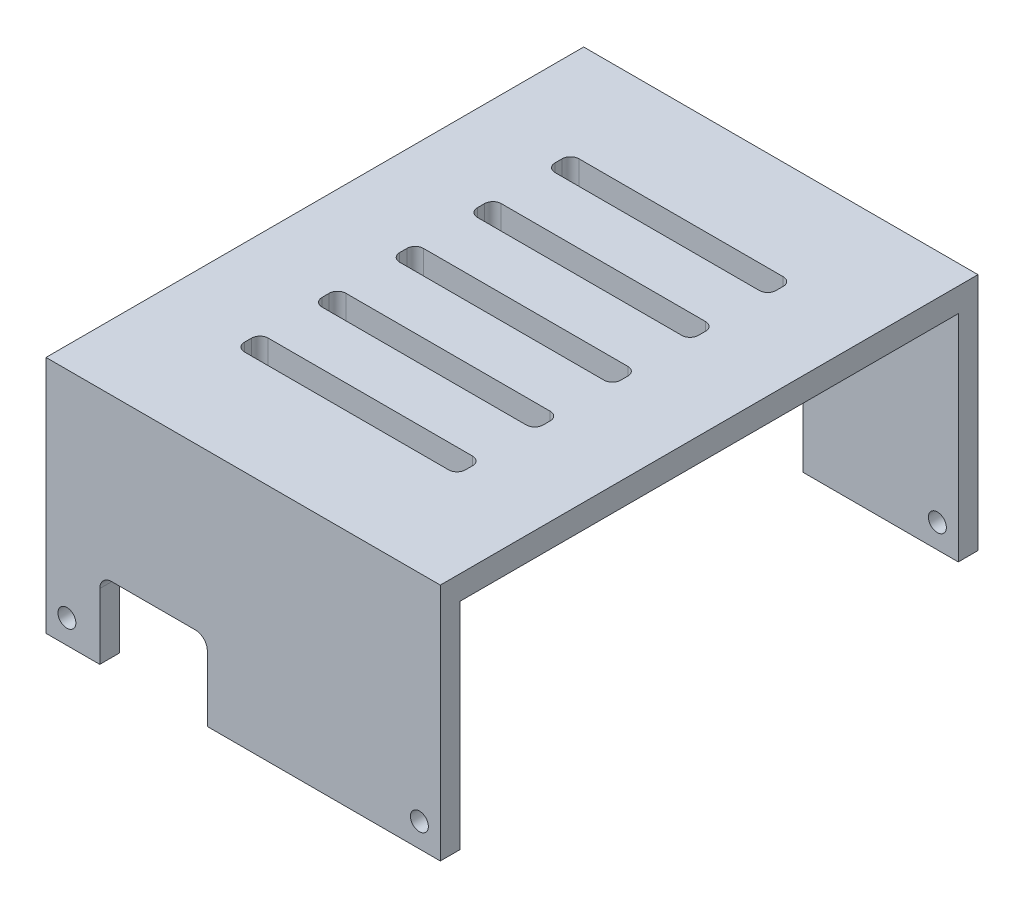
SolidWorks part; units mm, degrees
ref_plane "Front Plane" through (0, 0, 0) normal (0, 0, 1) x (1, 0, 0)
ref_plane "Top Plane" through (0, 0, 0) normal (0, 1, 0) x (1, 0, 0)
ref_plane "Right Plane" through (0, 0, 0) normal (1, 0, 0) x (0, 0, -1)
sketch "Sketch1" plane through (0, 0, 0) normal (0, 0, 1) x (1, 0, 0)
  line L1 (-33, -2) -> (33, -2)
  line L2 (-33, -2) -> (-33, 2)
  line L3 (-33, 2) -> (33, 2)
  line L4 (33, -2) -> (33, 2)
  line L5 (-33, -2) -> (33, 2) construction
  line L6 (-33, 2) -> (33, -2) construction
  point P0 (0, 0)
  dimension "D1" = 66
  dimension "D2" = 4
extrude "Boss-Extrude1" add sketch "Sketch1" along normal blind 90
sketch "Sketch2" plane through (0, 0, 90) normal (0, 0, 1) x (1, 0, 0)
  line L0 (-33, -2) -> (33, -2) construction
  line L1 (-33, -2) -> (33, -2)
  line L2 (-33, -2) -> (-33, -38)
  line L3 (-33, -38) -> (33, -38)
  line L4 (33, -2) -> (33, -38)
  point P6 (-30.5, -2)
  point P7 (30.2156, -2)
  point P8 (25.8419, -2)
  point P9 (0, 0)
  point P11 (30.5, -2)
  dimension "D3" = 36
extrude "Boss-Extrude2" add sketch "Sketch2" against normal blind 3.3
sketch "Sketch3" plane through (0, 0, 0) normal (0, 0, -1) x (-1, 0, 0)
  line L4 (33, -38) -> (33, -2)
  line L5 (33, -2) -> (-33, -2)
  line L6 (-33, -2) -> (-33, -38)
  line L7 (-33, -38) -> (33, -38)
  line L8 (33, -38) -> (33, -2)
  line L9 (33, -2) -> (-33, -2)
  line L10 (-33, -2) -> (-33, -38)
  line L11 (-33, -38) -> (33, -38)
  dimension "D1" = 0
extrude "Boss-Extrude3" add sketch "Sketch3" against normal blind 3.3
sketch "Sketch4" plane through (0, 0, 90) normal (0, 0, 1) x (1, 0, 0)
  line L0 (-33, -38) -> (33, -38) construction
  line L1 (-33, 2) -> (-33, -38) construction
  line L2 (33, -38) -> (33, 2) construction
  circle A0 centre (-29.5, -34) radius 1.5
  circle A1 centre (29.5, -34) radius 1.5
  point P4 (0, 0)
  dimension "D1" = 3
  dimension "D3" = 3.5
  dimension "D5" = 3
  dimension "D2" = 4
  dimension "D4" = 3.5
extrude "Cut-Extrude1" cut sketch "Sketch4" against normal through all
sketch "Sketch5" plane through (0, 0, 90) normal (0, 0, 1) x (1, 0, 0)
  line L0 (-15, -25) -> (-15, -38) construction
  line L1 (-24, -25) -> (-6, -25)
  line L2 (-24, -25) -> (-24, -38)
  line L3 (-24, -38) -> (-6, -38)
  line L4 (-6, -25) -> (-6, -38)
  line L5 (33, -38) -> (33, 2) construction
  line L6 (-33, -38) -> (33, -38) construction
  dimension "D1" = 18
  dimension "D2" = 48
  dimension "D3" = 13
extrude "Cut-Extrude2" cut sketch "Sketch5" against normal up to next
sketch "Sketch7" plane through (0, 0, 0) normal (0, 0, -1) x (-1, 0, 0)
  line L0 (-33, -38) -> (33, -38) construction
  line L1 (-7, -38) -> (23, -38)
  line L2 (-7, -38) -> (-7, -21)
  line L3 (-4, -18) -> (20, -18)
  line L4 (23, -38) -> (23, -21)
  line L5 (33, 2) -> (33, -38) construction
  arc A0 (20, -18) -> (23, -21) centre (20, -21) cw
  arc A1 (-4, -18) -> (-7, -21) centre (-4, -21) ccw
  point P10 (23, -18)
  point P13 (-7, -18)
  dimension "D4" = 3
  dimension "D1" = 30
  dimension "D2" = 20
  dimension "D3" = 10
extrude "Cut-Extrude4" cut sketch "Sketch7" against normal up to next
fillet "Fillet1" radius 2 2 edges at (-24, -25, 88.35) (-6, -25, 88.35)
sketch "Sketch8" plane through (0, 2, 0) normal (0, 1, 0) x (1, 0, 0)
  line L0 (33, 0) -> (-33, 0) construction
  line L1 (-17.2, -16.6) -> (17, -16.6)
  line L2 (-18.6, -18) -> (-18.6, -19.2)
  line L3 (-17.2, -20.6) -> (17, -20.6)
  line L4 (18.4, -18) -> (18.4, -19.2)
  line L5 (-33, -90) -> (-33, 0) construction
  line L6 (33, -90) -> (33, 0) construction
  arc A0 (18.4, -19.2) -> (17, -20.6) centre (17, -19.2) cw
  arc A1 (18.4, -18) -> (17, -16.6) centre (17, -18) ccw
  arc A2 (-17.2, -20.6) -> (-18.6, -19.2) centre (-17.2, -19.2) cw
  arc A3 (-17.2, -16.6) -> (-18.6, -18) centre (-17.2, -18) ccw
  point P4 (15.0053, -14.8749)
  point P9 (18.4, -20.6)
  point P12 (18.4, -16.6)
  point P17 (-18.6, -16.6)
  point P18 (0, 0)
  dimension "D4" = 1.4
  dimension "D1" = 90
  dimension "D2" = 4
  dimension "D3" = 37
  dimension "D5" = 18
  dimension "D6" = 16
extrude "Cut-Extrude5" cut sketch "Sketch8" against normal up to next
pattern_linear "LPattern1" count 5 spacing 13 along (0, 0, 1) of "Cut-Extrude5"
